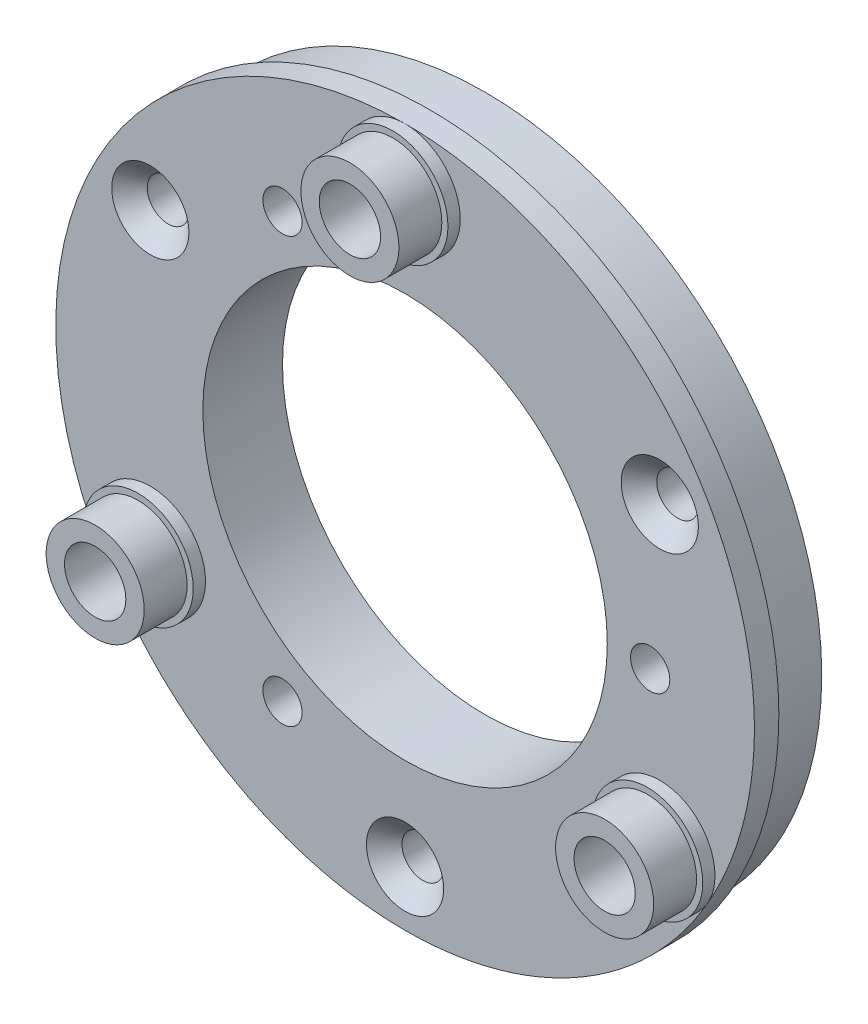
SolidWorks part; units mm, degrees
material "6061 Alloy"
ref_plane "Front Plane" through (0, 0, 0) normal (0, 0, 1) x (1, 0, 0)
ref_plane "Top Plane" through (0, 0, 0) normal (0, 1, 0) x (1, 0, 0)
ref_plane "Right Plane" through (0, 0, 0) normal (1, 0, 0) x (0, 0, -1)
sketch "Sketch1" plane through (0, 0, 0) normal (0, 0, 1) x (1, 0, 0)
  line L0 (0, 0) -> (0, 24) construction
  circle A0 centre (0, 0) radius 24 construction
  circle A2 centre (0, 0) radius 28.5
  circle A3 centre (0, 0) radius 19.5
  circle A4 centre (0, 24) radius 1.5 construction
  dimension "D1" = 48
  dimension "D4" = 3
  dimension "D2" = 4.5
  dimension "D3" = 4.5
extrude "Boss-Extrude1" add sketch "Sketch1" along normal blind 2
sketch "Sketch2" plane through (0, 0, 2) normal (0, 0, 1) x (1, 0, 0)
  circle A0 centre (0, 0) radius 24 construction
  circle A1 centre (0, 24) radius 1.5
  dimension "D1" = 48
  dimension "D2" = 3
extrude "Cut-Extrude1" cut sketch "Sketch2" against normal through all
pattern_circular "CirPattern1" count 3 over 360 about axis through (0, 0, 0) along (0, 0, 1) of "Cut-Extrude1"
sketch "Sketch3" plane through (0, 0, 0) normal (0, 0, -1) x (-1, 0, 0)
  circle A0 centre (0, 0) radius 27.5
  circle A1 centre (0, 0) radius 19.5
  circle A2 centre (0, 0) radius 19.5 construction
  dimension "D1" = 55
extrude "Boss-Extrude2" add sketch "Sketch3" along normal blind 4.5
sketch "Sketch4" plane through (0, 0, 2) normal (0, 0, 1) x (1, 0, 0)
  circle A0 centre (0, 24) radius 4.5
  circle A1 centre (0, 24) radius 2.5
  dimension "D1" = 9
  dimension "D2" = 5
extrude "Boss-Extrude3" add sketch "Sketch4" along normal blind 1
sketch "Sketch5" plane through (0, 0, 3) normal (0, 0, 1) x (1, 0, 0)
  circle A0 centre (0, 24) radius 4
  circle A1 centre (0, 24) radius 2.5
  dimension "D1" = 8
  dimension "D2" = 5
extrude "Boss-Extrude4" add sketch "Sketch5" along normal blind 3.5
pattern_circular "CirPattern6" count 3 over 360 about axis through (0, 0, 0) along (0, 0, 1) of "Boss-Extrude3", "Boss-Extrude4"
sketch "Sketch8" plane through (0, 0, 0) normal (0, 0, 1) x (1, 0, 0)
  circle A0 centre (0, 24) radius 1.5
  dimension "D1" = 3
extrude "Cut-Extrude4" cut sketch "Sketch8" against normal through all
pattern_circular "CirPattern7" count 3 over 360 about axis through (0, 0, 0) along (0, 0, 1) of "Cut-Extrude4"
sketch "Sketch9" plane through (0, 0, -4.5) normal (0, 0, -1) x (-1, 0, 0)
  line L0 (0, 0) -> (0, 24) construction
  line L1 (0, 0) -> (-20.7846, 12) construction
  circle A0 centre (0, 0) radius 24 construction
  circle A1 centre (-20.7846, 12) radius 1.5
  dimension "D2" = 3
  dimension "D1" = 60
extrude "Cut-Extrude5" cut sketch "Sketch9" against normal through all
pattern_circular "CirPattern8" count 6 over 360 about axis through (0, 0, -4.5) along (0, 0, -1) skipping 1, 3, 5 of "Cut-Extrude5"
sketch "Sketch10" plane through (0, 0, 2) normal (0, 0, 1) x (1, 0, 0)
  circle A1 centre (0, 24) radius 2.5
  circle A2 centre (0, 24) radius 2.5
  dimension "D1" = 0
extrude "Cut-Extrude6" cut sketch "Sketch10" against normal blind 3.5
pattern_circular "CirPattern9" count 3 over 360 of "Cut-Extrude6"
sketch "Sketch11" plane through (0, 0, -4.5) normal (0, 0, -1) x (-1, 0, 0)
  circle A0 centre (0, 0) radius 19.5
  circle A1 centre (0, 0) radius 19.5 construction
  circle A2 centre (0, 0) radius 16.5
  dimension "D1" = 3
extrude "Boss-Extrude5" add sketch "Sketch11" against normal up to surface (6.5 mm away) up to face at (1.5, -24, 2)
sketch "Sketch12" plane through (0, 0, -4.5) normal (0, 0, -1) x (-1, 0, 0)
  line L0 (0, 27.5) -> (0, 0) construction
  line L1 (0, 0) -> (13.75, 23.8157) construction
  circle A0 centre (0, 0) radius 20 construction
  circle A1 centre (0, 0) radius 27.5 construction
  circle A2 centre (0, 0) radius 27.5 construction
  circle A3 centre (10, 17.3205) radius 1.6
  dimension "D1" = 40
  dimension "D3" = 3.2
  dimension "D2" = 30
extrude "Cut-Extrude7" cut sketch "Sketch12" against normal blind 10
pattern_circular "CirPattern10" count 3 over 360 about axis through (0, 0, 0) along (0, 0, 1) of "Cut-Extrude7"
hole_wizard "CSK for M3 Flat Head Machine Screw1" positions "3DSketch1" profile "Sketch13" countersink size "M3" standard "ANSI Metric" end condition through all
sketch3d "3DSketch1"
  line L0 (-20.7846, 12, 2) -> (-20.7846, 12, -4.5) construction
  line L1 (20.7846, 12, 2) -> (20.7846, 12, -4.5) construction
  line L2 (0, -24, 2) -> (0, -24, -4.5) construction
  point P0 (-20.7846, 12, 2)
  point P5 (20.7846, 12, 2)
  point P9 (0, -24, 2)
sketch "Sketch13" plane through (-20.7846, 12, 2) normal (1, 0, 0) x (0, -1, 0)
  line L0 (0, 0) -> (0, 6.5)
  line L1 (0, 6.5) -> (1.7, 6.5)
  line L2 (1.7, 6.5) -> (1.7, 1.45)
  line L3 (1.7, 1.45) -> (3.15, 0)
  line L5 (3.15, 0) -> (0, 0)
  line L6 (-1.7, 1.45) -> (-3.15, 0) construction
  line L11 (0, -6.35) -> (0, 107.95) construction
  dimension "Thru Hole Dia." = 3.4
  dimension "Thru Hole Depth" = 6.5
  dimension "Near C'Sink Dia." = 6.3
  dimension "Near C'Sink Angle" = 90
